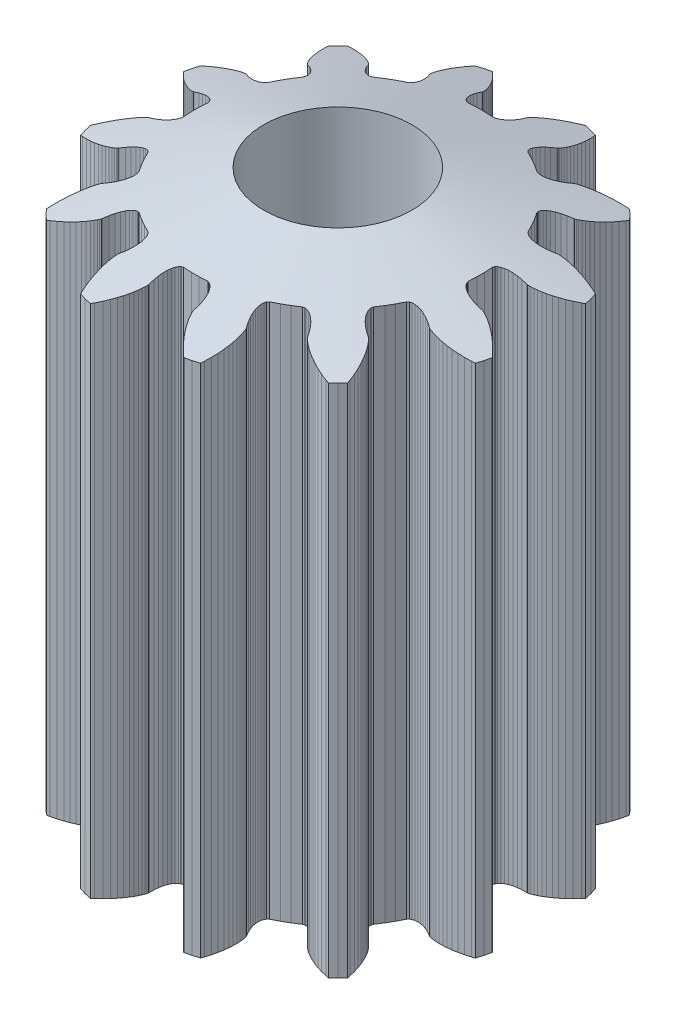
SolidWorks part; units mm, degrees
ref_plane "Front Plane" through (0, 0, 0) normal (0, 0, 1) x (1, 0, 0)
ref_plane "Top Plane" through (0, 0, 0) normal (0, 1, 0) x (1, 0, 0)
ref_plane "Right Plane" through (0, 0, 0) normal (1, 0, 0) x (0, 0, -1)
sketch "Sketch4" plane through (0, 0, 0) normal (0, 1, 0) x (1, 0, 0)
  line L0 (-8.5142, 2.5915) -> (-8.6005, 2.3068)
  line L1 (-8.6005, 2.3068) -> (-8.6681, 2.017)
  line L2 (-8.6681, 2.017) -> (-8.5825, 1.919)
  line L3 (-8.5825, 1.919) -> (-8.4064, 1.7373)
  line L4 (-8.4064, 1.7373) -> (-8.2355, 1.5786)
  line L5 (-8.2355, 1.5786) -> (-8.0717, 1.4418)
  line L6 (-8.0717, 1.4418) -> (-7.9169, 1.3256)
  line L7 (-7.9169, 1.3256) -> (-7.7726, 1.2287)
  line L8 (-7.7726, 1.2287) -> (-7.6405, 1.1497)
  line L9 (-7.6405, 1.1497) -> (-7.522, 1.087)
  line L10 (-7.522, 1.087) -> (-7.4183, 1.0389)
  line L11 (-7.4183, 1.0389) -> (-7.3306, 1.0037)
  line L12 (-7.3306, 1.0037) -> (-7.26, 0.9795)
  line L13 (-7.26, 0.9795) -> (-7.2073, 0.9645)
  line L14 (-7.2073, 0.9645) -> (-7.201, 0.9631)
  line L15 (-7.201, 0.9631) -> (-7.1713, 0.9658)
  line L16 (-7.1713, 0.9658) -> (-6.9676, 0.9668)
  line L17 (-6.9676, 0.9668) -> (-6.7838, 0.9501)
  line L18 (-6.7838, 0.9501) -> (-6.6212, 0.9179)
  line L19 (-6.6212, 0.9179) -> (-6.4809, 0.8724)
  line L20 (-6.4809, 0.8724) -> (-6.3638, 0.8157)
  line L21 (-6.3638, 0.8157) -> (-6.2706, 0.7503)
  line L22 (-6.2706, 0.7503) -> (-6.2018, 0.6785)
  line L23 (-6.2018, 0.6785) -> (-6.1577, 0.6025)
  line L24 (-6.1577, 0.6025) -> (-6.1387, 0.525)
  line L25 (-6.1387, 0.525) -> (-6.1577, 0.1615)
  line L26 (-6.1577, 0.1615) -> (-6.1577, -0.1615)
  line L27 (-6.1577, -0.1615) -> (-6.1387, -0.525)
  line L28 (-6.1387, -0.525) -> (-6.1577, -0.6025)
  line L29 (-6.1577, -0.6025) -> (-6.2018, -0.6785)
  line L30 (-6.2018, -0.6785) -> (-6.2706, -0.7503)
  line L31 (-6.2706, -0.7503) -> (-6.3638, -0.8157)
  line L32 (-6.3638, -0.8157) -> (-6.4809, -0.8724)
  line L33 (-6.4809, -0.8724) -> (-6.6212, -0.9179)
  line L34 (-6.6212, -0.9179) -> (-6.7838, -0.9501)
  line L35 (-6.7838, -0.9501) -> (-6.9676, -0.9668)
  line L36 (-6.9676, -0.9668) -> (-7.1713, -0.9658)
  line L37 (-7.1713, -0.9658) -> (-7.201, -0.9631)
  line L38 (-7.201, -0.9631) -> (-7.2073, -0.9645)
  line L39 (-7.2073, -0.9645) -> (-7.26, -0.9795)
  line L40 (-7.26, -0.9795) -> (-7.3306, -1.0037)
  line L41 (-7.3306, -1.0037) -> (-7.4183, -1.0389)
  line L42 (-7.4183, -1.0389) -> (-7.522, -1.087)
  line L43 (-7.522, -1.087) -> (-7.6405, -1.1497)
  line L44 (-7.6405, -1.1497) -> (-7.7726, -1.2287)
  line L45 (-7.7726, -1.2287) -> (-7.9169, -1.3256)
  line L46 (-7.9169, -1.3256) -> (-8.0717, -1.4418)
  line L47 (-8.0717, -1.4418) -> (-8.2355, -1.5786)
  line L48 (-8.2355, -1.5786) -> (-8.4064, -1.7373)
  line L49 (-8.4064, -1.7373) -> (-8.5825, -1.919)
  line L50 (-8.5825, -1.919) -> (-8.6681, -2.017)
  line L51 (-8.6681, -2.017) -> (-8.6005, -2.3068)
  line L52 (-8.6005, -2.3068) -> (-8.5142, -2.5915)
  line L53 (-8.5142, -2.5915) -> (-8.391, -2.6336)
  line L54 (-8.391, -2.6336) -> (-8.1477, -2.7029)
  line L55 (-8.1477, -2.7029) -> (-7.9203, -2.7549)
  line L56 (-7.9203, -2.7549) -> (-7.7101, -2.7915)
  line L57 (-7.7101, -2.7915) -> (-7.5179, -2.8147)
  line L58 (-7.5179, -2.8147) -> (-7.3445, -2.8264)
  line L59 (-7.3445, -2.8264) -> (-7.1906, -2.8288)
  line L60 (-7.1906, -2.8288) -> (-7.0566, -2.8239)
  line L61 (-7.0566, -2.8239) -> (-6.9428, -2.8137)
  line L62 (-6.9428, -2.8137) -> (-6.8492, -2.8003)
  line L63 (-6.8492, -2.8003) -> (-6.776, -2.7859)
  line L64 (-6.776, -2.7859) -> (-6.7228, -2.7726)
  line L65 (-6.7228, -2.7726) -> (-6.7167, -2.7707)
  line L66 (-6.7167, -2.7707) -> (-6.6923, -2.7535)
  line L67 (-6.6923, -2.7535) -> (-6.5163, -2.6507)
  line L68 (-6.5163, -2.6507) -> (-6.3489, -2.5733)
  line L69 (-6.3489, -2.5733) -> (-6.192, -2.5199)
  line L70 (-6.192, -2.5199) -> (-6.0477, -2.4892)
  line L71 (-6.0477, -2.4892) -> (-5.918, -2.4797)
  line L72 (-5.918, -2.4797) -> (-5.8045, -2.4897)
  line L73 (-5.8045, -2.4897) -> (-5.709, -2.5176)
  line L74 (-5.709, -2.5176) -> (-5.6329, -2.5613)
  line L75 (-5.6329, -2.5613) -> (-5.5776, -2.6189)
  line L76 (-5.5776, -2.6189) -> (-5.4124, -2.9433)
  line L77 (-5.4124, -2.9433) -> (-5.2509, -3.2229)
  line L78 (-5.2509, -3.2229) -> (-5.0526, -3.5282)
  line L79 (-5.0526, -3.5282) -> (-5.0304, -3.6049)
  line L80 (-5.0304, -3.6049) -> (-5.0305, -3.6927)
  line L81 (-5.0305, -3.6927) -> (-5.0542, -3.7893)
  line L82 (-5.0542, -3.7893) -> (-5.1022, -3.8926)
  line L83 (-5.1022, -3.8926) -> (-5.1753, -4.0002)
  line L84 (-5.1753, -4.0002) -> (-5.2741, -4.1098)
  line L85 (-5.2741, -4.1098) -> (-5.3987, -4.219)
  line L86 (-5.3987, -4.219) -> (-5.5496, -4.3253)
  line L87 (-5.5496, -4.3253) -> (-5.7265, -4.4263)
  line L88 (-5.7265, -4.4263) -> (-5.7536, -4.4388)
  line L89 (-5.7536, -4.4388) -> (-5.7583, -4.4432)
  line L90 (-5.7583, -4.4432) -> (-5.7965, -4.4825)
  line L91 (-5.7965, -4.4825) -> (-5.8455, -4.5388)
  line L92 (-5.8455, -4.5388) -> (-5.9039, -4.6131)
  line L93 (-5.9039, -4.6131) -> (-5.9696, -4.7066)
  line L94 (-5.9696, -4.7066) -> (-6.0409, -4.8202)
  line L95 (-6.0409, -4.8202) -> (-6.1158, -4.9546)
  line L96 (-6.1158, -4.9546) -> (-6.1923, -5.1107)
  line L97 (-6.1923, -5.1107) -> (-6.2683, -5.2887)
  line L98 (-6.2683, -5.2887) -> (-6.3417, -5.4891)
  line L99 (-6.3417, -5.4891) -> (-6.4104, -5.712)
  line L100 (-6.4104, -5.712) -> (-6.4721, -5.9574)
  line L101 (-6.4721, -5.9574) -> (-6.4972, -6.085)
  line L102 (-6.4972, -6.085) -> (-6.2938, -6.3022)
  line L103 (-6.2938, -6.3022) -> (-6.0766, -6.5056)
  line L104 (-6.0766, -6.5056) -> (-5.9489, -6.4805)
  line L105 (-5.9489, -6.4805) -> (-5.7035, -6.4188)
  line L106 (-5.7035, -6.4188) -> (-5.4806, -6.3502)
  line L107 (-5.4806, -6.3502) -> (-5.2802, -6.2768)
  line L108 (-5.2802, -6.2768) -> (-5.1022, -6.2008)
  line L109 (-5.1022, -6.2008) -> (-4.9462, -6.1243)
  line L110 (-4.9462, -6.1243) -> (-4.8117, -6.0494)
  line L111 (-4.8117, -6.0494) -> (-4.6981, -5.9781)
  line L112 (-4.6981, -5.9781) -> (-4.6046, -5.9123)
  line L113 (-4.6046, -5.9123) -> (-4.5303, -5.854)
  line L114 (-4.5303, -5.854) -> (-4.4741, -5.8049)
  line L115 (-4.4741, -5.8049) -> (-4.4347, -5.7667)
  line L116 (-4.4347, -5.7667) -> (-4.4304, -5.7621)
  line L117 (-4.4304, -5.7621) -> (-4.4178, -5.7349)
  line L118 (-4.4178, -5.7349) -> (-4.3168, -5.558)
  line L119 (-4.3168, -5.558) -> (-4.2105, -5.4072)
  line L120 (-4.2105, -5.4072) -> (-4.1013, -5.2825)
  line L121 (-4.1013, -5.2825) -> (-3.9917, -5.1838)
  line L122 (-3.9917, -5.1838) -> (-3.8841, -5.1107)
  line L123 (-3.8841, -5.1107) -> (-3.7809, -5.0626)
  line L124 (-3.7809, -5.0626) -> (-3.6842, -5.039)
  line L125 (-3.6842, -5.039) -> (-3.5965, -5.0388)
  line L126 (-3.5965, -5.0388) -> (-3.5198, -5.0611)
  line L127 (-3.5198, -5.0611) -> (-3.2145, -5.2594)
  line L128 (-3.2145, -5.2594) -> (-2.9348, -5.4208)
  line L129 (-2.9348, -5.4208) -> (-2.6105, -5.5861)
  line L130 (-2.6105, -5.5861) -> (-2.5528, -5.6414)
  line L131 (-2.5528, -5.6414) -> (-2.5091, -5.7174)
  line L132 (-2.5091, -5.7174) -> (-2.4813, -5.813)
  line L133 (-2.4813, -5.813) -> (-2.4712, -5.9264)
  line L134 (-2.4712, -5.9264) -> (-2.4807, -6.0562)
  line L135 (-2.4807, -6.0562) -> (-2.5114, -6.2004)
  line L136 (-2.5114, -6.2004) -> (-2.5648, -6.3573)
  line L137 (-2.5648, -6.3573) -> (-2.6423, -6.5248)
  line L138 (-2.6423, -6.5248) -> (-2.745, -6.7007)
  line L139 (-2.745, -6.7007) -> (-2.7622, -6.7252)
  line L140 (-2.7622, -6.7252) -> (-2.7641, -6.7313)
  line L141 (-2.7641, -6.7313) -> (-2.7775, -6.7844)
  line L142 (-2.7775, -6.7844) -> (-2.7919, -6.8577)
  line L143 (-2.7919, -6.8577) -> (-2.8052, -6.9512)
  line L144 (-2.8052, -6.9512) -> (-2.8154, -7.065)
  line L145 (-2.8154, -7.065) -> (-2.8204, -7.1991)
  line L146 (-2.8204, -7.1991) -> (-2.818, -7.353)
  line L147 (-2.818, -7.353) -> (-2.8062, -7.5263)
  line L148 (-2.8062, -7.5263) -> (-2.783, -7.7185)
  line L149 (-2.783, -7.7185) -> (-2.7464, -7.9288)
  line L150 (-2.7464, -7.9288) -> (-2.6944, -8.1561)
  line L151 (-2.6944, -8.1561) -> (-2.6252, -8.3995)
  line L152 (-2.6252, -8.3995) -> (-2.5831, -8.5226)
  line L153 (-2.5831, -8.5226) -> (-2.2983, -8.609)
  line L154 (-2.2983, -8.609) -> (-2.0085, -8.6766)
  line L155 (-2.0085, -8.6766) -> (-1.9105, -8.591)
  line L156 (-1.9105, -8.591) -> (-1.7288, -8.4148)
  line L157 (-1.7288, -8.4148) -> (-1.5701, -8.2439)
  line L158 (-1.5701, -8.2439) -> (-1.4333, -8.0802)
  line L159 (-1.4333, -8.0802) -> (-1.3171, -7.9253)
  line L160 (-1.3171, -7.9253) -> (-1.2203, -7.7811)
  line L161 (-1.2203, -7.7811) -> (-1.1413, -7.649)
  line L162 (-1.1413, -7.649) -> (-1.0785, -7.5304)
  line L163 (-1.0785, -7.5304) -> (-1.0304, -7.4268)
  line L164 (-1.0304, -7.4268) -> (-0.9952, -7.3391)
  line L165 (-0.9952, -7.3391) -> (-0.9711, -7.2685)
  line L166 (-0.9711, -7.2685) -> (-0.9561, -7.2157)
  line L167 (-0.9561, -7.2157) -> (-0.9547, -7.2095)
  line L168 (-0.9547, -7.2095) -> (-0.9573, -7.1797)
  line L169 (-0.9573, -7.1797) -> (-0.9583, -6.976)
  line L170 (-0.9583, -6.976) -> (-0.9417, -6.7922)
  line L171 (-0.9417, -6.7922) -> (-0.9095, -6.6297)
  line L172 (-0.9095, -6.6297) -> (-0.8639, -6.4894)
  line L173 (-0.8639, -6.4894) -> (-0.8073, -6.3723)
  line L174 (-0.8073, -6.3723) -> (-0.7419, -6.279)
  line L175 (-0.7419, -6.279) -> (-0.67, -6.2102)
  line L176 (-0.67, -6.2102) -> (-0.5941, -6.1662)
  line L177 (-0.5941, -6.1662) -> (-0.5165, -6.1471)
  line L178 (-0.5165, -6.1471) -> (-0.153, -6.1662)
  line L179 (-0.153, -6.1662) -> (0.1699, -6.1662)
  line L180 (0.1699, -6.1662) -> (0.5334, -6.1471)
  line L181 (0.5334, -6.1471) -> (0.611, -6.1662)
  line L182 (0.611, -6.1662) -> (0.6869, -6.2102)
  line L183 (0.6869, -6.2102) -> (0.7588, -6.279)
  line L184 (0.7588, -6.279) -> (0.8242, -6.3723)
  line L185 (0.8242, -6.3723) -> (0.8808, -6.4894)
  line L186 (0.8808, -6.4894) -> (0.9264, -6.6297)
  line L187 (0.9264, -6.6297) -> (0.9586, -6.7922)
  line L188 (0.9586, -6.7922) -> (0.9752, -6.976)
  line L189 (0.9752, -6.976) -> (0.9742, -7.1797)
  line L190 (0.9742, -7.1797) -> (0.9716, -7.2095)
  line L191 (0.9716, -7.2095) -> (0.973, -7.2157)
  line L192 (0.973, -7.2157) -> (0.988, -7.2685)
  line L193 (0.988, -7.2685) -> (1.0121, -7.3391)
  line L194 (1.0121, -7.3391) -> (1.0474, -7.4268)
  line L195 (1.0474, -7.4268) -> (1.0954, -7.5304)
  line L196 (1.0954, -7.5304) -> (1.1582, -7.649)
  line L197 (1.1582, -7.649) -> (1.2372, -7.7811)
  line L198 (1.2372, -7.7811) -> (1.334, -7.9253)
  line L199 (1.334, -7.9253) -> (1.4502, -8.0802)
  line L200 (1.4502, -8.0802) -> (1.587, -8.2439)
  line L201 (1.587, -8.2439) -> (1.7457, -8.4148)
  line L202 (1.7457, -8.4148) -> (1.9274, -8.591)
  line L203 (1.9274, -8.591) -> (2.0254, -8.6766)
  line L204 (2.0254, -8.6766) -> (2.3152, -8.609)
  line L205 (2.3152, -8.609) -> (2.6, -8.5226)
  line L206 (2.6, -8.5226) -> (2.6421, -8.3995)
  line L207 (2.6421, -8.3995) -> (2.7113, -8.1561)
  line L208 (2.7113, -8.1561) -> (2.7633, -7.9288)
  line L209 (2.7633, -7.9288) -> (2.7999, -7.7185)
  line L210 (2.7999, -7.7185) -> (2.8231, -7.5263)
  line L211 (2.8231, -7.5263) -> (2.8349, -7.353)
  line L212 (2.8349, -7.353) -> (2.8373, -7.1991)
  line L213 (2.8373, -7.1991) -> (2.8323, -7.065)
  line L214 (2.8323, -7.065) -> (2.8221, -6.9512)
  line L215 (2.8221, -6.9512) -> (2.8088, -6.8577)
  line L216 (2.8088, -6.8577) -> (2.7944, -6.7844)
  line L217 (2.7944, -6.7844) -> (2.781, -6.7313)
  line L218 (2.781, -6.7313) -> (2.7791, -6.7252)
  line L219 (2.7791, -6.7252) -> (2.7619, -6.7007)
  line L220 (2.7619, -6.7007) -> (2.6592, -6.5248)
  line L221 (2.6592, -6.5248) -> (2.5817, -6.3573)
  line L222 (2.5817, -6.3573) -> (2.5283, -6.2004)
  line L223 (2.5283, -6.2004) -> (2.4976, -6.0562)
  line L224 (2.4976, -6.0562) -> (2.4881, -5.9264)
  line L225 (2.4881, -5.9264) -> (2.4982, -5.813)
  line L226 (2.4982, -5.813) -> (2.526, -5.7174)
  line L227 (2.526, -5.7174) -> (2.5697, -5.6414)
  line L228 (2.5697, -5.6414) -> (2.6274, -5.5861)
  line L229 (2.6274, -5.5861) -> (2.9517, -5.4208)
  line L230 (2.9517, -5.4208) -> (3.2314, -5.2594)
  line L231 (3.2314, -5.2594) -> (3.5367, -5.0611)
  line L232 (3.5367, -5.0611) -> (3.6134, -5.0388)
  line L233 (3.6134, -5.0388) -> (3.7011, -5.039)
  line L234 (3.7011, -5.039) -> (3.7978, -5.0626)
  line L235 (3.7978, -5.0626) -> (3.901, -5.1107)
  line L236 (3.901, -5.1107) -> (4.0087, -5.1838)
  line L237 (4.0087, -5.1838) -> (4.1182, -5.2825)
  line L238 (4.1182, -5.2825) -> (4.2274, -5.4072)
  line L239 (4.2274, -5.4072) -> (4.3337, -5.558)
  line L240 (4.3337, -5.558) -> (4.4347, -5.7349)
  line L241 (4.4347, -5.7349) -> (4.4473, -5.7621)
  line L242 (4.4473, -5.7621) -> (4.4516, -5.7667)
  line L243 (4.4516, -5.7667) -> (4.491, -5.8049)
  line L244 (4.491, -5.8049) -> (4.5472, -5.854)
  line L245 (4.5472, -5.854) -> (4.6215, -5.9123)
  line L246 (4.6215, -5.9123) -> (4.715, -5.9781)
  line L247 (4.715, -5.9781) -> (4.8286, -6.0494)
  line L248 (4.8286, -6.0494) -> (4.9631, -6.1243)
  line L249 (4.9631, -6.1243) -> (5.1191, -6.2008)
  line L250 (5.1191, -6.2008) -> (5.2971, -6.2768)
  line L251 (5.2971, -6.2768) -> (5.4975, -6.3502)
  line L252 (5.4975, -6.3502) -> (5.7204, -6.4188)
  line L253 (5.7204, -6.4188) -> (5.9658, -6.4805)
  line L254 (5.9658, -6.4805) -> (6.0935, -6.5056)
  line L255 (6.0935, -6.5056) -> (6.3107, -6.3022)
  line L256 (6.3107, -6.3022) -> (6.5141, -6.085)
  line L257 (6.5141, -6.085) -> (6.489, -5.9574)
  line L258 (6.489, -5.9574) -> (6.4273, -5.712)
  line L259 (6.4273, -5.712) -> (6.3586, -5.4891)
  line L260 (6.3586, -5.4891) -> (6.2852, -5.2887)
  line L261 (6.2852, -5.2887) -> (6.2092, -5.1107)
  line L262 (6.2092, -5.1107) -> (6.1327, -4.9546)
  line L263 (6.1327, -4.9546) -> (6.0578, -4.8202)
  line L264 (6.0578, -4.8202) -> (5.9865, -4.7066)
  line L265 (5.9865, -4.7066) -> (5.9208, -4.6131)
  line L266 (5.9208, -4.6131) -> (5.8624, -4.5388)
  line L267 (5.8624, -4.5388) -> (5.8134, -4.4825)
  line L268 (5.8134, -4.4825) -> (5.7752, -4.4432)
  line L269 (5.7752, -4.4432) -> (5.7705, -4.4388)
  line L270 (5.7705, -4.4388) -> (5.7434, -4.4263)
  line L271 (5.7434, -4.4263) -> (5.5665, -4.3253)
  line L272 (5.5665, -4.3253) -> (5.4156, -4.219)
  line L273 (5.4156, -4.219) -> (5.291, -4.1098)
  line L274 (5.291, -4.1098) -> (5.1922, -4.0002)
  line L275 (5.1922, -4.0002) -> (5.1191, -3.8926)
  line L276 (5.1191, -3.8926) -> (5.0711, -3.7893)
  line L277 (5.0711, -3.7893) -> (5.0474, -3.6927)
  line L278 (5.0474, -3.6927) -> (5.0473, -3.6049)
  line L279 (5.0473, -3.6049) -> (5.0695, -3.5282)
  line L280 (5.0695, -3.5282) -> (5.2678, -3.2229)
  line L281 (5.2678, -3.2229) -> (5.4293, -2.9433)
  line L282 (5.4293, -2.9433) -> (5.5945, -2.6189)
  line L283 (5.5945, -2.6189) -> (5.6498, -2.5613)
  line L284 (5.6498, -2.5613) -> (5.7259, -2.5176)
  line L285 (5.7259, -2.5176) -> (5.8214, -2.4897)
  line L286 (5.8214, -2.4897) -> (5.9349, -2.4797)
  line L287 (5.9349, -2.4797) -> (6.0646, -2.4892)
  line L288 (6.0646, -2.4892) -> (6.2089, -2.5199)
  line L289 (6.2089, -2.5199) -> (6.3658, -2.5733)
  line L290 (6.3658, -2.5733) -> (6.5332, -2.6507)
  line L291 (6.5332, -2.6507) -> (6.7092, -2.7535)
  line L292 (6.7092, -2.7535) -> (6.7336, -2.7707)
  line L293 (6.7336, -2.7707) -> (6.7397, -2.7726)
  line L294 (6.7397, -2.7726) -> (6.7929, -2.7859)
  line L295 (6.7929, -2.7859) -> (6.8661, -2.8003)
  line L296 (6.8661, -2.8003) -> (6.9597, -2.8137)
  line L297 (6.9597, -2.8137) -> (7.0735, -2.8239)
  line L298 (7.0735, -2.8239) -> (7.2075, -2.8288)
  line L299 (7.2075, -2.8288) -> (7.3614, -2.8264)
  line L300 (7.3614, -2.8264) -> (7.5348, -2.8147)
  line L301 (7.5348, -2.8147) -> (7.727, -2.7915)
  line L302 (7.727, -2.7915) -> (7.9372, -2.7549)
  line L303 (7.9372, -2.7549) -> (8.1646, -2.7029)
  line L304 (8.1646, -2.7029) -> (8.4079, -2.6336)
  line L305 (8.4079, -2.6336) -> (8.5311, -2.5915)
  line L306 (8.5311, -2.5915) -> (8.6174, -2.3068)
  line L307 (8.6174, -2.3068) -> (8.685, -2.017)
  line L308 (8.685, -2.017) -> (8.5994, -1.919)
  line L309 (8.5994, -1.919) -> (8.4233, -1.7373)
  line L310 (8.4233, -1.7373) -> (8.2524, -1.5786)
  line L311 (8.2524, -1.5786) -> (8.0886, -1.4418)
  line L312 (8.0886, -1.4418) -> (7.9338, -1.3256)
  line L313 (7.9338, -1.3256) -> (7.7895, -1.2287)
  line L314 (7.7895, -1.2287) -> (7.6574, -1.1497)
  line L315 (7.6574, -1.1497) -> (7.5389, -1.087)
  line L316 (7.5389, -1.087) -> (7.4352, -1.0389)
  line L317 (7.4352, -1.0389) -> (7.3475, -1.0037)
  line L318 (7.3475, -1.0037) -> (7.2769, -0.9795)
  line L319 (7.2769, -0.9795) -> (7.2242, -0.9645)
  line L320 (7.2242, -0.9645) -> (7.218, -0.9631)
  line L321 (7.218, -0.9631) -> (7.1882, -0.9658)
  line L322 (7.1882, -0.9658) -> (6.9845, -0.9668)
  line L323 (6.9845, -0.9668) -> (6.8007, -0.9501)
  line L324 (6.8007, -0.9501) -> (6.6381, -0.9179)
  line L325 (6.6381, -0.9179) -> (6.4978, -0.8724)
  line L326 (6.4978, -0.8724) -> (6.3807, -0.8157)
  line L327 (6.3807, -0.8157) -> (6.2875, -0.7503)
  line L328 (6.2875, -0.7503) -> (6.2187, -0.6785)
  line L329 (6.2187, -0.6785) -> (6.1747, -0.6025)
  line L330 (6.1747, -0.6025) -> (6.1556, -0.525)
  line L331 (6.1556, -0.525) -> (6.1747, -0.1615)
  line L332 (6.1747, -0.1615) -> (6.1747, 0.1615)
  line L333 (6.1747, 0.1615) -> (6.1556, 0.525)
  line L334 (6.1556, 0.525) -> (6.1747, 0.6025)
  line L335 (6.1747, 0.6025) -> (6.2187, 0.6785)
  line L336 (6.2187, 0.6785) -> (6.2875, 0.7503)
  line L337 (6.2875, 0.7503) -> (6.3807, 0.8157)
  line L338 (6.3807, 0.8157) -> (6.4978, 0.8724)
  line L339 (6.4978, 0.8724) -> (6.6381, 0.9179)
  line L340 (6.6381, 0.9179) -> (6.8007, 0.9501)
  line L341 (6.8007, 0.9501) -> (6.9845, 0.9668)
  line L342 (6.9845, 0.9668) -> (7.1882, 0.9658)
  line L343 (7.1882, 0.9658) -> (7.218, 0.9631)
  line L344 (7.218, 0.9631) -> (7.2242, 0.9645)
  line L345 (7.2242, 0.9645) -> (7.2769, 0.9795)
  line L346 (7.2769, 0.9795) -> (7.3475, 1.0037)
  line L347 (7.3475, 1.0037) -> (7.4352, 1.0389)
  line L348 (7.4352, 1.0389) -> (7.5389, 1.087)
  line L349 (7.5389, 1.087) -> (7.6574, 1.1497)
  line L350 (7.6574, 1.1497) -> (7.7895, 1.2287)
  line L351 (7.7895, 1.2287) -> (7.9338, 1.3256)
  line L352 (7.9338, 1.3256) -> (8.0886, 1.4418)
  line L353 (8.0886, 1.4418) -> (8.2524, 1.5786)
  line L354 (8.2524, 1.5786) -> (8.4233, 1.7373)
  line L355 (8.4233, 1.7373) -> (8.5994, 1.919)
  line L356 (8.5994, 1.919) -> (8.685, 2.017)
  line L357 (8.685, 2.017) -> (8.6174, 2.3068)
  line L358 (8.6174, 2.3068) -> (8.5311, 2.5915)
  line L359 (8.5311, 2.5915) -> (8.4079, 2.6336)
  line L360 (8.4079, 2.6336) -> (8.1646, 2.7029)
  line L361 (8.1646, 2.7029) -> (7.9372, 2.7549)
  line L362 (7.9372, 2.7549) -> (7.727, 2.7915)
  line L363 (7.727, 2.7915) -> (7.5348, 2.8147)
  line L364 (7.5348, 2.8147) -> (7.3614, 2.8264)
  line L365 (7.3614, 2.8264) -> (7.2075, 2.8288)
  line L366 (7.2075, 2.8288) -> (7.0735, 2.8239)
  line L367 (7.0735, 2.8239) -> (6.9597, 2.8137)
  line L368 (6.9597, 2.8137) -> (6.8661, 2.8003)
  line L369 (6.8661, 2.8003) -> (6.7929, 2.7859)
  line L370 (6.7929, 2.7859) -> (6.7397, 2.7726)
  line L371 (6.7397, 2.7726) -> (6.7336, 2.7707)
  line L372 (6.7336, 2.7707) -> (6.7092, 2.7535)
  line L373 (6.7092, 2.7535) -> (6.5332, 2.6507)
  line L374 (6.5332, 2.6507) -> (6.3658, 2.5733)
  line L375 (6.3658, 2.5733) -> (6.2089, 2.5199)
  line L376 (6.2089, 2.5199) -> (6.0646, 2.4892)
  line L377 (6.0646, 2.4892) -> (5.9349, 2.4797)
  line L378 (5.9349, 2.4797) -> (5.8214, 2.4897)
  line L379 (5.8214, 2.4897) -> (5.7259, 2.5176)
  line L380 (5.7259, 2.5176) -> (5.6498, 2.5613)
  line L381 (5.6498, 2.5613) -> (5.5945, 2.6189)
  line L382 (5.5945, 2.6189) -> (5.4293, 2.9433)
  line L383 (5.4293, 2.9433) -> (5.2678, 3.2229)
  line L384 (5.2678, 3.2229) -> (5.0695, 3.5282)
  line L385 (5.0695, 3.5282) -> (5.0473, 3.6049)
  line L386 (5.0473, 3.6049) -> (5.0474, 3.6927)
  line L387 (5.0474, 3.6927) -> (5.0711, 3.7893)
  line L388 (5.0711, 3.7893) -> (5.1191, 3.8926)
  line L389 (5.1191, 3.8926) -> (5.1922, 4.0002)
  line L390 (5.1922, 4.0002) -> (5.291, 4.1098)
  line L391 (5.291, 4.1098) -> (5.4156, 4.219)
  line L392 (5.4156, 4.219) -> (5.5665, 4.3253)
  line L393 (5.5665, 4.3253) -> (5.7434, 4.4263)
  line L394 (5.7434, 4.4263) -> (5.7705, 4.4388)
  line L395 (5.7705, 4.4388) -> (5.7752, 4.4432)
  line L396 (5.7752, 4.4432) -> (5.8134, 4.4825)
  line L397 (5.8134, 4.4825) -> (5.8624, 4.5388)
  line L398 (5.8624, 4.5388) -> (5.9208, 4.6131)
  line L399 (5.9208, 4.6131) -> (5.9865, 4.7066)
  line L400 (5.9865, 4.7066) -> (6.0578, 4.8202)
  line L401 (6.0578, 4.8202) -> (6.1327, 4.9546)
  line L402 (6.1327, 4.9546) -> (6.2092, 5.1107)
  line L403 (6.2092, 5.1107) -> (6.2852, 5.2887)
  line L404 (6.2852, 5.2887) -> (6.3586, 5.4891)
  line L405 (6.3586, 5.4891) -> (6.4273, 5.712)
  line L406 (6.4273, 5.712) -> (6.489, 5.9574)
  line L407 (6.489, 5.9574) -> (6.5141, 6.085)
  line L408 (6.5141, 6.085) -> (6.3107, 6.3022)
  line L409 (6.3107, 6.3022) -> (6.0935, 6.5056)
  line L410 (6.0935, 6.5056) -> (5.9658, 6.4805)
  line L411 (5.9658, 6.4805) -> (5.7204, 6.4188)
  line L412 (5.7204, 6.4188) -> (5.4975, 6.3502)
  line L413 (5.4975, 6.3502) -> (5.2971, 6.2768)
  line L414 (5.2971, 6.2768) -> (5.1191, 6.2008)
  line L415 (5.1191, 6.2008) -> (4.9631, 6.1243)
  line L416 (4.9631, 6.1243) -> (4.8286, 6.0494)
  line L417 (4.8286, 6.0494) -> (4.715, 5.9781)
  line L418 (4.715, 5.9781) -> (4.6215, 5.9123)
  line L419 (4.6215, 5.9123) -> (4.5472, 5.854)
  line L420 (4.5472, 5.854) -> (4.491, 5.8049)
  line L421 (4.491, 5.8049) -> (4.4516, 5.7667)
  line L422 (4.4516, 5.7667) -> (4.4473, 5.7621)
  line L423 (4.4473, 5.7621) -> (4.4347, 5.7349)
  line L424 (4.4347, 5.7349) -> (4.3337, 5.558)
  line L425 (4.3337, 5.558) -> (4.2274, 5.4072)
  line L426 (4.2274, 5.4072) -> (4.1182, 5.2825)
  line L427 (4.1182, 5.2825) -> (4.0087, 5.1838)
  line L428 (4.0087, 5.1838) -> (3.901, 5.1107)
  line L429 (3.901, 5.1107) -> (3.7978, 5.0626)
  line L430 (3.7978, 5.0626) -> (3.7011, 5.039)
  line L431 (3.7011, 5.039) -> (3.6134, 5.0388)
  line L432 (3.6134, 5.0388) -> (3.5367, 5.0611)
  line L433 (3.5367, 5.0611) -> (3.2314, 5.2594)
  line L434 (3.2314, 5.2594) -> (2.9517, 5.4208)
  line L435 (2.9517, 5.4208) -> (2.6274, 5.5861)
  line L436 (2.6274, 5.5861) -> (2.5697, 5.6414)
  line L437 (2.5697, 5.6414) -> (2.526, 5.7174)
  line L438 (2.526, 5.7174) -> (2.4982, 5.813)
  line L439 (2.4982, 5.813) -> (2.4881, 5.9264)
  line L440 (2.4881, 5.9264) -> (2.4976, 6.0562)
  line L441 (2.4976, 6.0562) -> (2.5283, 6.2004)
  line L442 (2.5283, 6.2004) -> (2.5817, 6.3573)
  line L443 (2.5817, 6.3573) -> (2.6592, 6.5248)
  line L444 (2.6592, 6.5248) -> (2.7619, 6.7007)
  line L445 (2.7619, 6.7007) -> (2.7791, 6.7252)
  line L446 (2.7791, 6.7252) -> (2.781, 6.7313)
  line L447 (2.781, 6.7313) -> (2.7944, 6.7844)
  line L448 (2.7944, 6.7844) -> (2.8088, 6.8577)
  line L449 (2.8088, 6.8577) -> (2.8221, 6.9512)
  line L450 (2.8221, 6.9512) -> (2.8323, 7.065)
  line L451 (2.8323, 7.065) -> (2.8373, 7.1991)
  line L452 (2.8373, 7.1991) -> (2.8349, 7.353)
  line L453 (2.8349, 7.353) -> (2.8231, 7.5263)
  line L454 (2.8231, 7.5263) -> (2.7999, 7.7185)
  line L455 (2.7999, 7.7185) -> (2.7633, 7.9288)
  line L456 (2.7633, 7.9288) -> (2.7113, 8.1561)
  line L457 (2.7113, 8.1561) -> (2.6421, 8.3995)
  line L458 (2.6421, 8.3995) -> (2.6, 8.5226)
  line L459 (2.6, 8.5226) -> (2.3152, 8.609)
  line L460 (2.3152, 8.609) -> (2.0254, 8.6766)
  line L461 (2.0254, 8.6766) -> (1.9274, 8.591)
  line L462 (1.9274, 8.591) -> (1.7457, 8.4148)
  line L463 (1.7457, 8.4148) -> (1.587, 8.2439)
  line L464 (1.587, 8.2439) -> (1.4502, 8.0802)
  line L465 (1.4502, 8.0802) -> (1.334, 7.9253)
  line L466 (1.334, 7.9253) -> (1.2372, 7.7811)
  line L467 (1.2372, 7.7811) -> (1.1582, 7.649)
  line L468 (1.1582, 7.649) -> (1.0954, 7.5304)
  line L469 (1.0954, 7.5304) -> (1.0474, 7.4268)
  line L470 (1.0474, 7.4268) -> (1.0121, 7.3391)
  line L471 (1.0121, 7.3391) -> (0.988, 7.2685)
  line L472 (0.988, 7.2685) -> (0.973, 7.2157)
  line L473 (0.973, 7.2157) -> (0.9716, 7.2095)
  line L474 (0.9716, 7.2095) -> (0.9742, 7.1797)
  line L475 (0.9742, 7.1797) -> (0.9752, 6.976)
  line L476 (0.9752, 6.976) -> (0.9586, 6.7922)
  line L477 (0.9586, 6.7922) -> (0.9264, 6.6297)
  line L478 (0.9264, 6.6297) -> (0.8808, 6.4894)
  line L479 (0.8808, 6.4894) -> (0.8242, 6.3723)
  line L480 (0.8242, 6.3723) -> (0.7588, 6.279)
  line L481 (0.7588, 6.279) -> (0.6869, 6.2102)
  line L482 (0.6869, 6.2102) -> (0.611, 6.1662)
  line L483 (0.611, 6.1662) -> (0.5334, 6.1471)
  line L484 (0.5334, 6.1471) -> (0.1699, 6.1662)
  line L485 (0.1699, 6.1662) -> (-0.153, 6.1662)
  line L486 (-0.153, 6.1662) -> (-0.5165, 6.1471)
  line L487 (-0.5165, 6.1471) -> (-0.5941, 6.1662)
  line L488 (-0.5941, 6.1662) -> (-0.67, 6.2102)
  line L489 (-0.67, 6.2102) -> (-0.7419, 6.279)
  line L490 (-0.7419, 6.279) -> (-0.8073, 6.3723)
  line L491 (-0.8073, 6.3723) -> (-0.8639, 6.4894)
  line L492 (-0.8639, 6.4894) -> (-0.9095, 6.6297)
  line L493 (-0.9095, 6.6297) -> (-0.9417, 6.7922)
  line L494 (-0.9417, 6.7922) -> (-0.9583, 6.976)
  line L495 (-0.9583, 6.976) -> (-0.9573, 7.1797)
  line L496 (-0.9573, 7.1797) -> (-0.9547, 7.2095)
  line L497 (-0.9547, 7.2095) -> (-0.9561, 7.2157)
  line L498 (-0.9561, 7.2157) -> (-0.9711, 7.2685)
  line L499 (-0.9711, 7.2685) -> (-0.9952, 7.3391)
  line L500 (-0.9952, 7.3391) -> (-1.0304, 7.4268)
  line L501 (-1.0304, 7.4268) -> (-1.0785, 7.5304)
  line L502 (-1.0785, 7.5304) -> (-1.1413, 7.649)
  line L503 (-1.1413, 7.649) -> (-1.2203, 7.7811)
  line L504 (-1.2203, 7.7811) -> (-1.3171, 7.9253)
  line L505 (-1.3171, 7.9253) -> (-1.4333, 8.0802)
  line L506 (-1.4333, 8.0802) -> (-1.5701, 8.2439)
  line L507 (-1.5701, 8.2439) -> (-1.7288, 8.4148)
  line L508 (-1.7288, 8.4148) -> (-1.9105, 8.591)
  line L509 (-1.9105, 8.591) -> (-2.0085, 8.6766)
  line L510 (-2.0085, 8.6766) -> (-2.2983, 8.609)
  line L511 (-2.2983, 8.609) -> (-2.5831, 8.5226)
  line L512 (-2.5831, 8.5226) -> (-2.6252, 8.3995)
  line L513 (-2.6252, 8.3995) -> (-2.6944, 8.1561)
  line L514 (-2.6944, 8.1561) -> (-2.7464, 7.9288)
  line L515 (-2.7464, 7.9288) -> (-2.783, 7.7185)
  line L516 (-2.783, 7.7185) -> (-2.8062, 7.5263)
  line L517 (-2.8062, 7.5263) -> (-2.818, 7.353)
  line L518 (-2.818, 7.353) -> (-2.8204, 7.1991)
  line L519 (-2.8204, 7.1991) -> (-2.8154, 7.065)
  line L520 (-2.8154, 7.065) -> (-2.8052, 6.9512)
  line L521 (-2.8052, 6.9512) -> (-2.7919, 6.8577)
  line L522 (-2.7919, 6.8577) -> (-2.7775, 6.7844)
  line L523 (-2.7775, 6.7844) -> (-2.7641, 6.7313)
  line L524 (-2.7641, 6.7313) -> (-2.7622, 6.7252)
  line L525 (-2.7622, 6.7252) -> (-2.745, 6.7007)
  line L526 (-2.745, 6.7007) -> (-2.6423, 6.5248)
  line L527 (-2.6423, 6.5248) -> (-2.5648, 6.3573)
  line L528 (-2.5648, 6.3573) -> (-2.5114, 6.2004)
  line L529 (-2.5114, 6.2004) -> (-2.4807, 6.0562)
  line L530 (-2.4807, 6.0562) -> (-2.4712, 5.9264)
  line L531 (-2.4712, 5.9264) -> (-2.4813, 5.813)
  line L532 (-2.4813, 5.813) -> (-2.5091, 5.7174)
  line L533 (-2.5091, 5.7174) -> (-2.5528, 5.6414)
  line L534 (-2.5528, 5.6414) -> (-2.6105, 5.5861)
  line L535 (-2.6105, 5.5861) -> (-2.9348, 5.4208)
  line L536 (-2.9348, 5.4208) -> (-3.2145, 5.2594)
  line L537 (-3.2145, 5.2594) -> (-3.5198, 5.0611)
  line L538 (-3.5198, 5.0611) -> (-3.5965, 5.0388)
  line L539 (-3.5965, 5.0388) -> (-3.6842, 5.039)
  line L540 (-3.6842, 5.039) -> (-3.7809, 5.0626)
  line L541 (-3.7809, 5.0626) -> (-3.8841, 5.1107)
  line L542 (-3.8841, 5.1107) -> (-3.9917, 5.1838)
  line L543 (-3.9917, 5.1838) -> (-4.1013, 5.2825)
  line L544 (-4.1013, 5.2825) -> (-4.2105, 5.4072)
  line L545 (-4.2105, 5.4072) -> (-4.3168, 5.558)
  line L546 (-4.3168, 5.558) -> (-4.4178, 5.7349)
  line L547 (-4.4178, 5.7349) -> (-4.4304, 5.7621)
  line L548 (-4.4304, 5.7621) -> (-4.4347, 5.7667)
  line L549 (-4.4347, 5.7667) -> (-4.4741, 5.8049)
  line L550 (-4.4741, 5.8049) -> (-4.5303, 5.854)
  line L551 (-4.5303, 5.854) -> (-4.6046, 5.9123)
  line L552 (-4.6046, 5.9123) -> (-4.6981, 5.9781)
  line L553 (-4.6981, 5.9781) -> (-4.8117, 6.0494)
  line L554 (-4.8117, 6.0494) -> (-4.9462, 6.1243)
  line L555 (-4.9462, 6.1243) -> (-5.1022, 6.2008)
  line L556 (-5.1022, 6.2008) -> (-5.2802, 6.2768)
  line L557 (-5.2802, 6.2768) -> (-5.4806, 6.3502)
  line L558 (-5.4806, 6.3502) -> (-5.7035, 6.4188)
  line L559 (-5.7035, 6.4188) -> (-5.9489, 6.4805)
  line L560 (-5.9489, 6.4805) -> (-6.0766, 6.5056)
  line L561 (-6.0766, 6.5056) -> (-6.2938, 6.3022)
  line L562 (-6.2938, 6.3022) -> (-6.4972, 6.085)
  line L563 (-6.4972, 6.085) -> (-6.4721, 5.9574)
  line L564 (-6.4721, 5.9574) -> (-6.4104, 5.712)
  line L565 (-6.4104, 5.712) -> (-6.3417, 5.4891)
  line L566 (-6.3417, 5.4891) -> (-6.2683, 5.2887)
  line L567 (-6.2683, 5.2887) -> (-6.1923, 5.1107)
  line L568 (-6.1923, 5.1107) -> (-6.1158, 4.9546)
  line L569 (-6.1158, 4.9546) -> (-6.0409, 4.8202)
  line L570 (-6.0409, 4.8202) -> (-5.9696, 4.7066)
  line L571 (-5.9696, 4.7066) -> (-5.9039, 4.6131)
  line L572 (-5.9039, 4.6131) -> (-5.8455, 4.5388)
  line L573 (-5.8455, 4.5388) -> (-5.7965, 4.4825)
  line L574 (-5.7965, 4.4825) -> (-5.7583, 4.4432)
  line L575 (-5.7583, 4.4432) -> (-5.7536, 4.4388)
  line L576 (-5.7536, 4.4388) -> (-5.7265, 4.4263)
  line L577 (-5.7265, 4.4263) -> (-5.5496, 4.3253)
  line L578 (-5.5496, 4.3253) -> (-5.3987, 4.219)
  line L579 (-5.3987, 4.219) -> (-5.2741, 4.1098)
  line L580 (-5.2741, 4.1098) -> (-5.1753, 4.0002)
  line L581 (-5.1753, 4.0002) -> (-5.1022, 3.8926)
  line L582 (-5.1022, 3.8926) -> (-5.0542, 3.7893)
  line L583 (-5.0542, 3.7893) -> (-5.0305, 3.6927)
  line L584 (-5.0305, 3.6927) -> (-5.0304, 3.6049)
  line L585 (-5.0304, 3.6049) -> (-5.0526, 3.5282)
  line L586 (-5.0526, 3.5282) -> (-5.2509, 3.2229)
  line L587 (-5.2509, 3.2229) -> (-5.4124, 2.9433)
  line L588 (-5.4124, 2.9433) -> (-5.5776, 2.6189)
  line L589 (-5.5776, 2.6189) -> (-5.6329, 2.5613)
  line L590 (-5.6329, 2.5613) -> (-5.709, 2.5176)
  line L591 (-5.709, 2.5176) -> (-5.8045, 2.4897)
  line L592 (-5.8045, 2.4897) -> (-5.918, 2.4797)
  line L593 (-5.918, 2.4797) -> (-6.0477, 2.4892)
  line L594 (-6.0477, 2.4892) -> (-6.192, 2.5199)
  line L595 (-6.192, 2.5199) -> (-6.3489, 2.5733)
  line L596 (-6.3489, 2.5733) -> (-6.5163, 2.6507)
  line L597 (-6.5163, 2.6507) -> (-6.6923, 2.7535)
  line L598 (-6.6923, 2.7535) -> (-6.7167, 2.7707)
  line L599 (-6.7167, 2.7707) -> (-6.7228, 2.7726)
  line L600 (-6.7228, 2.7726) -> (-6.776, 2.7859)
  line L601 (-6.776, 2.7859) -> (-6.8492, 2.8003)
  line L602 (-6.8492, 2.8003) -> (-6.9428, 2.8137)
  line L603 (-6.9428, 2.8137) -> (-7.0566, 2.8239)
  line L604 (-7.0566, 2.8239) -> (-7.1906, 2.8288)
  line L605 (-7.1906, 2.8288) -> (-7.3445, 2.8264)
  line L606 (-7.3445, 2.8264) -> (-7.5179, 2.8147)
  line L607 (-7.5179, 2.8147) -> (-7.7101, 2.7915)
  line L608 (-7.7101, 2.7915) -> (-7.9203, 2.7549)
  line L609 (-7.9203, 2.7549) -> (-8.1477, 2.7029)
  line L610 (-8.1477, 2.7029) -> (-8.391, 2.6336)
  line L611 (-8.391, 2.6336) -> (-8.5142, 2.5915)
extrude "Boss-Extrude3" add sketch "Sketch4" along normal blind 24
sketch "Sketch5" plane through (0, 0, 0) normal (0, -1, 0) x (1, 0, 0)
  line L0 (2.25, 2.2754) -> (2.25, -2.2754)
  line L1 (2.25, -2.2754) -> (-2.25, -2.2754) construction
  line L2 (-2.25, -2.2754) -> (-2.25, 2.2754)
  line L3 (-2.25, 2.2754) -> (2.25, 2.2754) construction
  circle A0 centre (0, 0) radius 3.2
  dimension "D1" = 6.4
  dimension "D2" = 4.5
extrude "Cut-Extrude2" cut sketch "Sketch5" against normal through all contours L0 A0 L2 | L0 A0 | L2 A0
sketch "Sketch6" plane through (0, 0, 0) normal (0, 0, 1) x (1, 0, 0)
  line L0 (3.2, 24) -> (9.7, 24)
  line L1 (9.7, 24) -> (9.7, 22)
  line L2 (9.7, 22) -> (3.2, 24)
  dimension "D1" = 6.5
  dimension "D2" = 2
sketch "Sketch7" plane through (0, 0, 0) normal (1, 0, 0) x (0, 0, -1)
  line L0 (0, 0) -> (0, 30.485) construction
revolve "Cut-Revolve1" cut sketch "Sketch6" angle 360 about L0
